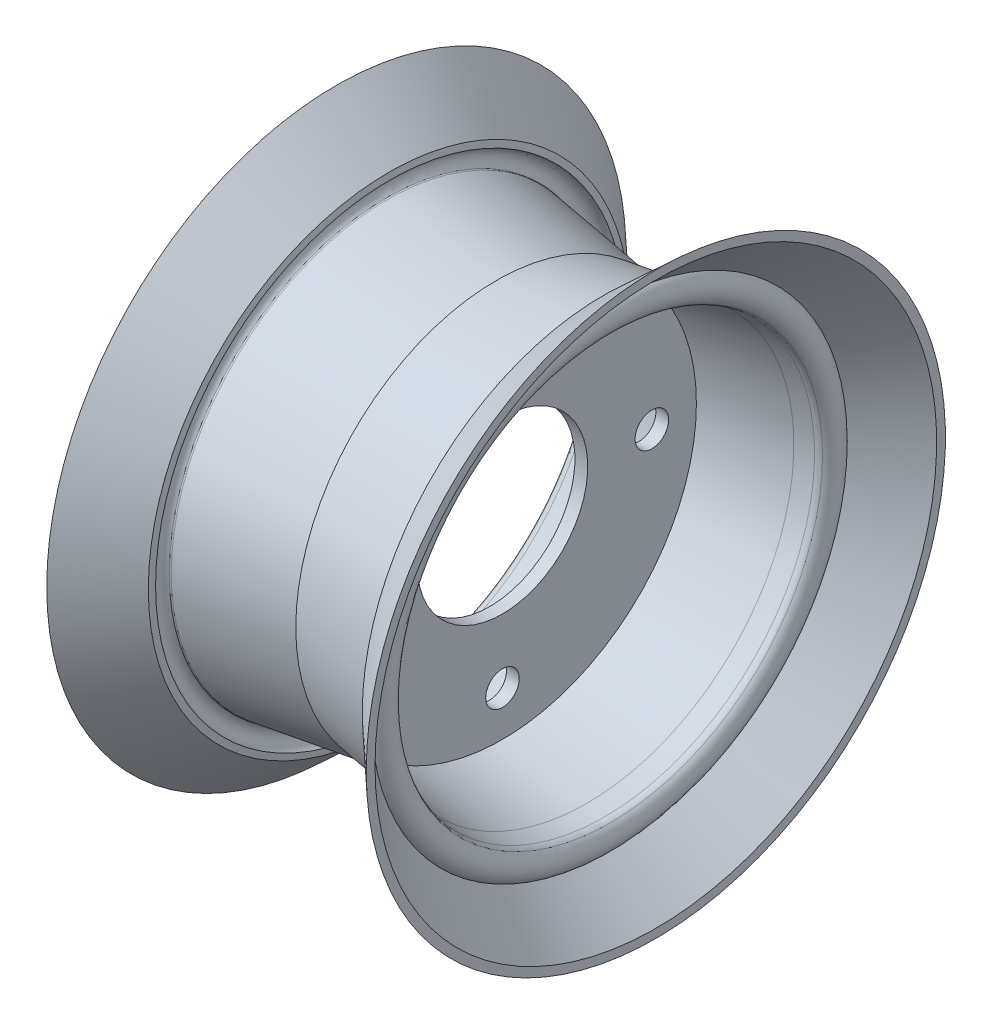
SolidWorks part; units mm, degrees
ref_plane "Front Plane" through (0, 0, 0) normal (0, 0, 1) x (1, 0, 0)
ref_plane "Top Plane" through (0, 0, 0) normal (0, 1, 0) x (1, 0, 0)
ref_plane "Right Plane" through (0, 0, 0) normal (1, 0, 0) x (0, 0, -1)
sketch "Sketch1" plane through (0, 0, 0) normal (0, 0, 1) x (1, 0, 0)
  line L0 (-124.1425, 0) -> (114.4069, 0) construction
  line L1 (21.2998, 48.5774) -> (1.5, 45.5)
  line L2 (0.75, 0) -> (0.75, 59.9147) construction
  line L3 (0.75, 0) -> (0.75, 59.9147) construction
  line L4 (0, 47) -> (0, 20)
  line L5 (1.5, 45.5) -> (1.5, 20)
  line L6 (25.4724, 49.25) -> (21.2998, 48.5774)
  line L8 (1.5, 20) -> (0, 20)
  line L9 (26.5381, 55.8163) -> (37.4843, 65.8917)
  line L10 (25.1, 56.5) -> (37.4843, 67.9497)
  line L11 (37.4843, 67.9497) -> (37.4843, 65.8917)
  line L12 (0, 47) -> (25.4724, 50.75)
  line L14 (25.1, 56.5) -> (24.8971, 55)
  arc A0 (26.824, 49.7759) -> (26.5381, 55.8163) centre (24.164, 52.6769) ccw
  arc A1 (26.824, 49.7759) -> (25.4724, 49.25) centre (25.4724, 51.25) cw
  arc A4 (25.8103, 50.8815) -> (25.4724, 50.75) centre (25.4724, 51.25) cw
  arc A5 (25.8103, 50.8815) -> (24.8971, 55) centre (24.164, 52.6769) ccw
  point P10 (26.5299, 55.8225)
  point P36 (0.75, 0)
  dimension "D1" = 2
revolve "Revolve1" add sketch "Sketch1" angle 360 about L0
sketch "Sketch3" plane through (0, 0, 0) normal (1, 0, 0) x (0, 0, -1)
  circle A0 centre (0, 35.052) radius 3.937
  circle A1 centre (35.052, 0) radius 3.937
  circle A2 centre (0, -35.052) radius 3.937
  circle A3 centre (-35.052, 0) radius 3.937
  point P0 (0, 35.052)
  point P12 (0, 0)
  dimension "D1" = 4
extrude "Cut-Extrude1" cut sketch "Sketch3" along normal up to surface (1.5 mm away) up to face at (1.5, 0, 45.5)
mirror "Mirror1" about plane through (0, 47, 0) normal (1, 0, 0) of "Revolve1", "Cut-Extrude1"
